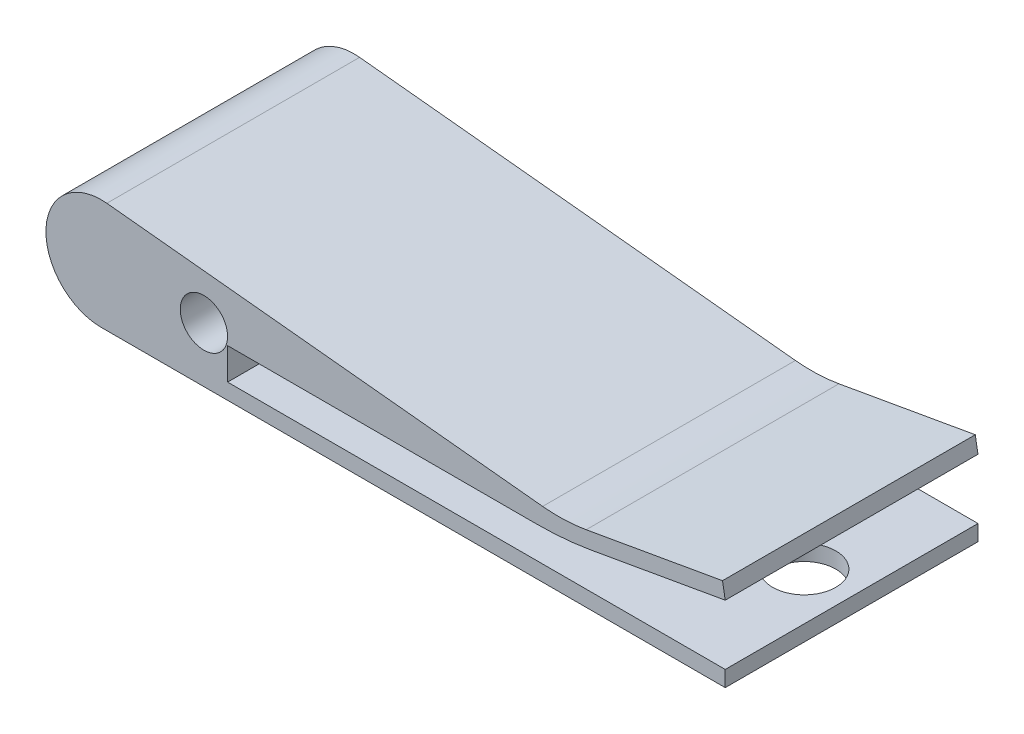
SolidWorks part; units mm, degrees
material "Acciaio inossidabile fuso"
ref_plane "Piano frontale" through (0, 0, 0) normal (0, 0, 1) x (1, 0, 0)
ref_plane "Piano superiore" through (0, 0, 0) normal (0, 1, 0) x (1, 0, 0)
ref_plane "Piano destro" through (0, 0, 0) normal (1, 0, 0) x (0, 0, -1)
sketch "Schizzo1" plane through (0, 0, 0) normal (0, 0, 1) x (1, 0, 0)
  line L0 (3.5, 0) -> (43, 0)
  line L1 (43, 0) -> (43, 1)
  line L2 (43, 1) -> (5.9495, 1)
  line L4 (6.9641, 3) -> (32.8264, 3)
  line L5 (32.8264, 3) -> (43, 4.7939)
  line L6 (43, 4.7939) -> (42.8264, 5.7787)
  line L9 (42.8264, 5.7787) -> (32.8264, 4.0154)
  line L10 (32.8264, 4.0154) -> (3.8565, 6.9818)
  line L12 (43, 1) -> (43, 4.7939) construction
  line L13 (32.8264, 4.0154) -> (32.8264, 3) construction
  line L14 (11.5, 3) -> (11.5, 1)
  arc A0 (5.9495, 1) -> (6.9641, 3) centre (3.5, 3.5) ccw
  arc A1 (3.8565, 6.9818) -> (3.5, 0) centre (3.5, 3.5) ccw
  dimension "D1" = 7
  dimension "D2" = 43
  dimension "D3" = 1
  dimension "D4" = 2
  dimension "D5" = 80
  dimension "D6" = 10
  dimension "D7" = 3.5
  dimension "D8" = 8
extrude "Estrusione-Estrusione1" add sketch "Schizzo1" along normal blind 16 contours A0 L2 L14 L4
fillet "Raccordo1" radius 10 1 edges at (32.8264, 4.0154, 8)
fillet "Raccordo2" radius 20 1 edges at (32.8264, 3, 8)
sketch "Schizzo3" plane through (0, 0, 16) normal (0, 0, 1) x (1, 0, 0)
  circle A0 centre (10, 3.5) radius 1.5
  dimension "D1" = 3
  dimension "D2" = 10
  dimension "D3" = 3.5
extrude "Taglio-Estrusione1" cut sketch "Schizzo3" against normal blind 16
sketch "Schizzo4" plane through (0, 0, 0) normal (0, -1, 0) x (1, 0, 0)
  line L0 (3.5, 0) -> (43, 0) construction
  line L1 (15, 8) -> (40, 8) construction
  line L3 (0, 16) -> (0, 0) construction
  circle A0 centre (40, 8) radius 2
  circle A1 centre (15, 8) radius 2
  dimension "D2" = 4
  dimension "D1" = 15
  dimension "D3" = 8
  dimension "D4" = 25
extrude "Taglio-Estrusione2" cut sketch "Schizzo4" against normal blind 1
